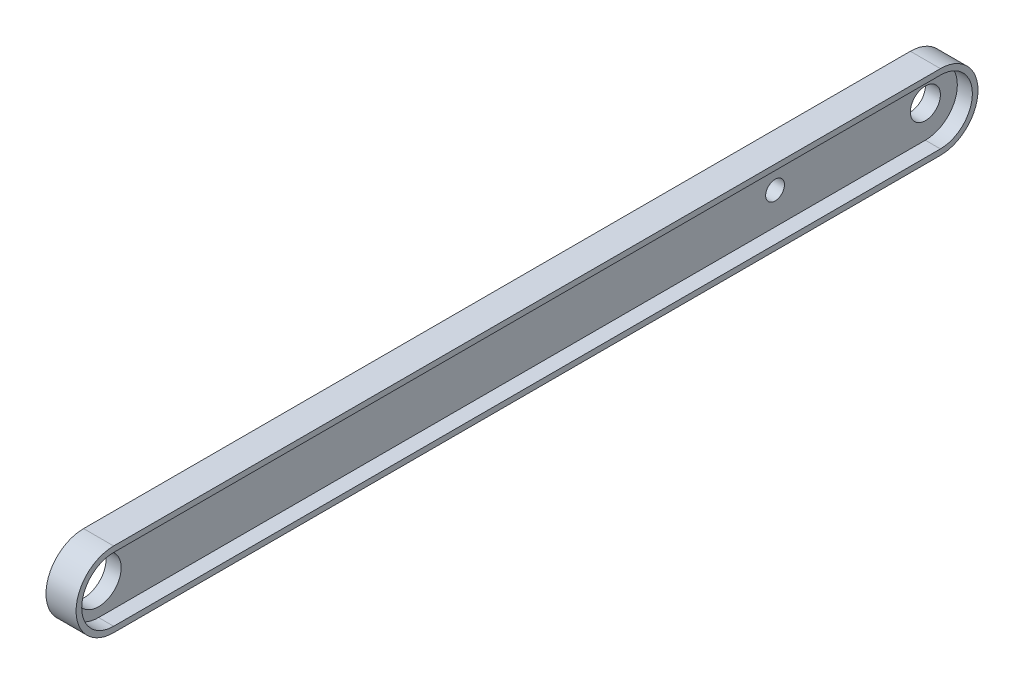
SolidWorks part; units mm, degrees
ref_plane "Front Plane" through (0, 0, 0) normal (0, 0, 1) x (1, 0, 0)
ref_plane "Top Plane" through (0, 0, 0) normal (0, 1, 0) x (1, 0, 0)
ref_plane "Right Plane" through (0, 0, 0) normal (1, 0, 0) x (0, 0, -1)
sketch "Sketch1" plane through (0, 0, 0) normal (1, 0, 0) x (0, 0, -1)
  line L0 (0, 0) -> (110, 0)
  line L1 (0, 10) -> (110, 10)
  line L2 (110, 5) -> (0, 5) construction
  arc A0 (0, 10) -> (0, 0) centre (0, 5) ccw
  arc A1 (110, 10) -> (110, 0) centre (110, 5) cw
  circle A2 centre (0, 5) radius 3
  circle A3 centre (110, 5) radius 2
  circle A4 centre (90, 5) radius 1.25
  dimension "D4" = 5
  dimension "D5" = 5
  dimension "D6" = 6
  dimension "D7" = 4
  dimension "D8" = 2.5
  dimension "D1" = 110
  dimension "D2" = 10
  dimension "D3" = 5
  dimension "D9" = 20
extrude "Boss-Extrude1" add sketch "Sketch1" along normal blind 2
sketch "Sketch2" plane through (2, 0, 0) normal (1, 0, 0) x (0, 0, -1)
  line L0 (0, 9.25) -> (110, 9.25)
  line L2 (0, 0.75) -> (110, 0.75)
  line L3 (0, 0) -> (110, 0) construction
  line L4 (0, 0) -> (110, 0)
  line L5 (110, 10) -> (0, 10)
  arc A0 (0, 9.25) -> (0, 0.75) centre (0, 5) ccw
  arc A1 (0, 10) -> (0, 0) centre (0, 5) ccw
  arc A2 (0, 10) -> (0, 0) centre (0, 5) ccw construction
  arc A3 (110, 9.25) -> (110, 0.75) centre (110, 5) cw
  arc A4 (110, 10) -> (110, 0) centre (110, 5) cw
  arc A5 (110, 0) -> (110, 10) centre (110, 5) ccw construction
  dimension "D5" = 5
  dimension "D2" = 4.25
  dimension "D6" = 4.25
  dimension "D1" = 110
  dimension "D3" = 110
  dimension "D4" = 8.5
extrude "Boss-Extrude3" add sketch "Sketch2" along normal blind 2
